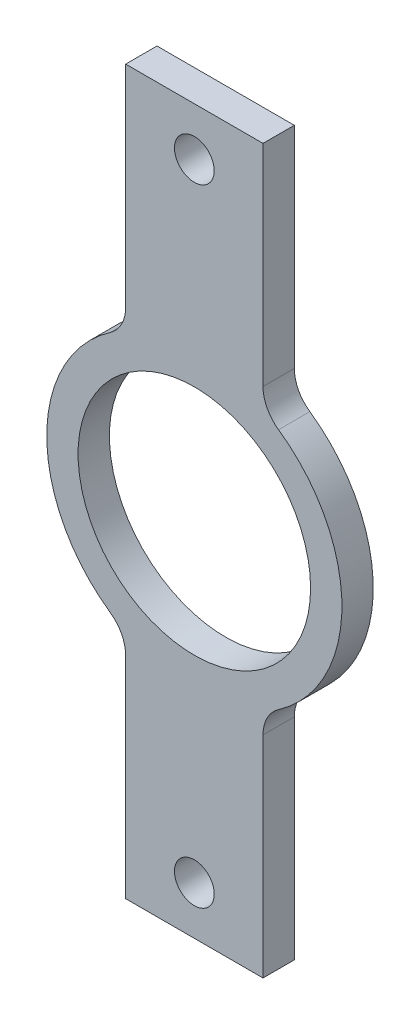
SolidWorks part; units mm, degrees
material "6061 合金"
ref_plane "前视基准面" through (0, 0, 0) normal (0, 0, 1) x (1, 0, 0)
ref_plane "上视基准面" through (0, 0, 0) normal (0, 1, 0) x (1, 0, 0)
ref_plane "右视基准面" through (0, 0, 0) normal (1, 0, 0) x (0, 0, -1)
sketch "草图1" plane through (0, 0, 0) normal (0, 0, 1) x (1, 0, 0)
  line L0 (0, 0) -> (0, 30) construction
  line L1 (0, 0) -> (0, -30) construction
  line L2 (0, 30) -> (-5.7, 30)
  line L3 (-5.7, 30) -> (-5.7, 10.8431)
  line L4 (-5.7, -30) -> (0, -30)
  line L5 (0, -30) -> (5.7, -30)
  line L6 (5.7, -30) -> (5.7, -10.8431)
  line L7 (5.7, 30) -> (0, 30)
  line L8 (-5.7, -10.8431) -> (-5.7, -30)
  line L9 (5.7, 10.8431) -> (5.7, 30)
  circle A0 centre (0, 0) radius 9.65
  arc A1 (-5.7, 10.8431) -> (-5.7, -10.8431) centre (0, 0) ccw
  circle A2 centre (0, 26) radius 1.65
  circle A3 centre (0, -26) radius 1.65
  arc A4 (5.7, -10.8431) -> (5.7, 10.8431) centre (0, 0) ccw
  dimension "D1" = 19.3
  dimension "D2" = 24.5
  dimension "D7" = 3.3
  dimension "D8" = 26
  dimension "D9" = 3.3
  dimension "D10" = 26
  dimension "D3" = 30
  dimension "D4" = 30
  dimension "D5" = 5.7
  dimension "D6" = 5.7
extrude "凸台-拉伸1" add sketch "草图1" along normal blind 2.6
fillet "圆角1" radius 3 4 edges at (5.7, -10.8431, 1.3) (-5.7, -10.8431, 1.3) (-5.7, 10.8431, 1.3) (5.7, 10.8431, 1.3)
